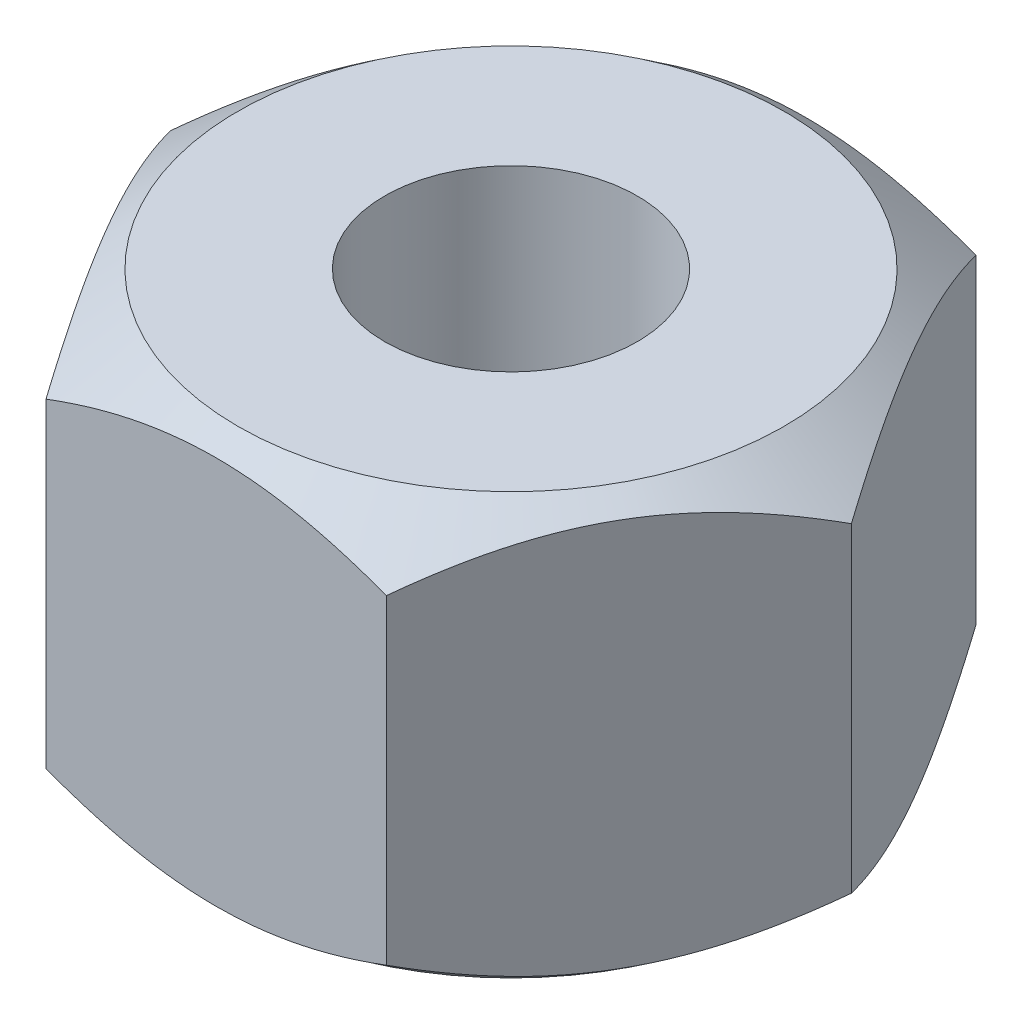
SolidWorks part; units mm, degrees
ref_plane "Front Plane" through (0, 0, 0) normal (0, 0, 1) x (1, 0, 0)
ref_plane "Top Plane" through (0, 0, 0) normal (0, 1, 0) x (1, 0, 0)
ref_plane "Right Plane" through (0, 0, 0) normal (1, 0, 0) x (0, 0, -1)
sketch "Sketch3" plane through (0, 0, 0) normal (0, 0, 1) x (1, 0, 0)
  line L0 (0, 2.5) -> (0, -2.5)
  point P4 (0, 0)
  dimension "D1" = 5
sketch "Sketch1" plane through (0, 0, 0) normal (0, 1, 0) x (1, 0, 0)
  line L1 (4.0415, 0) -> (2.0207, 3.5)
  line L2 (2.0207, 3.5) -> (-2.0207, 3.5)
  line L3 (-2.0207, 3.5) -> (-4.0415, 0)
  line L4 (-4.0415, 0) -> (-2.0207, -3.5)
  line L5 (-2.0207, -3.5) -> (2.0207, -3.5)
  line L6 (2.0207, -3.5) -> (4.0415, 0)
  circle A0 centre (0, 0) radius 3.5 construction
  dimension "D1" = 7
extrude "Boss-Extrude1" add sketch "Sketch1" along normal mid plane 5
sketch "Sketch2" plane through (0, 0, 0) normal (0, 0, 1) x (1, 0, 0)
  line L0 (4.0415, 2.5) -> (3.2415, 2.5)
  line L1 (3.2415, 2.5) -> (4.0415, 1.9)
  line L2 (4.0415, 2.5) -> (4.0415, -2.5) construction
  line L3 (4.0415, 1.9) -> (4.0415, 2.5)
  line L4 (4.0415, -2.5) -> (4.0415, -1.9)
  line L5 (4.0415, -1.9) -> (3.2415, -2.5)
  line L6 (3.2415, -2.5) -> (4.0415, -2.5)
  dimension "D1" = 3.8
  dimension "D2" = 0.8
revolve "Cut-Revolve1" cut sketch "Sketch2" angle 360 about L0
sketch "Sketch4" plane through (0, 2.5, 0) normal (0, 1, 0) x (1, 0, 0)
  circle A0 centre (0, 0) radius 1.5
  dimension "D1" = 3
extrude "Cut-Extrude1" cut sketch "Sketch4" against normal up to surface (5 mm away) up to face at (0, -2.5, 3.2415)
sketch "Sketch5" plane through (-3.0311, 0, -1.75) normal (-0.866, 0, -0.5) x (-0.5, 0, 0.866)
  circle A0 centre (0, 0) radius 1.35
  dimension "D1" = 2.7
extrude "Boss-Extrude2" add sketch "Sketch5" along normal blind 0.6
sketch "Sketch6" plane through (-3.5507, 0, -2.05) normal (-0.866, 0, -0.5) x (-0.5, 0, 0.866)
  circle A0 centre (0, 0) radius 0.85
  dimension "D1" = 1.7
extrude "Cut-Extrude3" cut sketch "Sketch6" against normal blind 1
